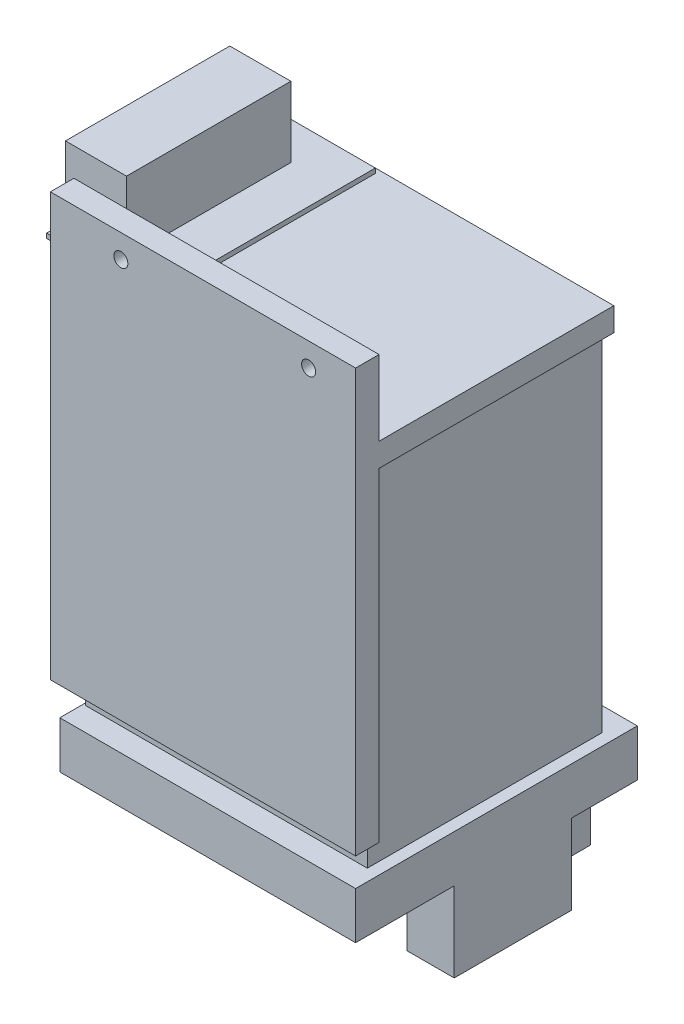
SolidWorks part; units mm, degrees
ref_plane "Front Plane" through (0, 0, 0) normal (0, 0, 1) x (1, 0, 0)
ref_plane "Top Plane" through (0, 0, 0) normal (0, 1, 0) x (1, 0, 0)
ref_plane "Right Plane" through (0, 0, 0) normal (1, 0, 0) x (0, 0, -1)
sketch "Sketch2" plane through (0, 0, 0) normal (0, 0, 1) x (1, 0, 0)
  line L1 (32.5, -45) -> (-32.5, -45)
  line L2 (32.5, -45) -> (32.5, 45)
  line L3 (32.5, 45) -> (-32.5, 45)
  line L4 (-32.5, -45) -> (-32.5, 45)
  line L5 (32.5, -45) -> (-32.5, 45) construction
  line L6 (32.5, 45) -> (-32.5, -45) construction
  circle A0 centre (-17.5, 40) radius 1.5
  circle A1 centre (22.5, 40) radius 1.5
  point P0 (0, 0)
  dimension "D3" = 40
  dimension "D4" = 3
  dimension "D5" = 5
  dimension "D6" = 10
  dimension "D1" = 65
  dimension "D2" = 90
extrude "Boss-Extrude1" add sketch "Sketch2" along normal blind 5
sketch "Sketch3" plane through (0, 0, 0) normal (0, 0, -1) x (-1, 0, 0)
  line L0 (-32.5, -45) -> (-32.5, 45) construction
  line L1 (32.5, 24) -> (-32.5, 24)
  line L2 (32.5, 24) -> (32.5, 29)
  line L3 (32.5, 29) -> (-32.5, 29)
  line L4 (-32.5, 24) -> (-32.5, 29)
  line L5 (32.5, 24) -> (-32.5, 29) construction
  line L6 (32.5, 29) -> (-32.5, 24) construction
  line L7 (-32.5, 45) -> (32.5, 45) construction
  point P0 (0, 26.5)
  dimension "D1" = 5
  dimension "D2" = 16
extrude "Boss-Extrude2" add sketch "Sketch3" along normal blind 50
sketch "Sketch4" plane through (0, 29, 0) normal (0, 1, 0) x (1, 0, 0)
  line L0 (-55, 0) -> (55, 0) construction
  line L1 (-17.2872, 2) -> (-40.2872, 2)
  line L2 (-17.2872, 2) -> (-17.2872, 49)
  line L3 (-17.2872, 49) -> (-40.2872, 49)
  line L4 (-40.2872, 2) -> (-40.2872, 49)
  line L5 (-17.2872, 2) -> (-40.2872, 49) construction
  line L6 (-17.2872, 49) -> (-40.2872, 2) construction
  point P0 (-28.7872, 25.5)
  dimension "D1" = 23
  dimension "D2" = 47
  dimension "D3" = 2
extrude "Boss-Extrude3" add sketch "Sketch4" along normal blind 1
sketch "Sketch5" plane through (0, 30, 0) normal (0, 1, 0) x (1, 0, 0)
  line L0 (-17.2872, 49) -> (-32.5, 49) construction
  line L1 (-40.2872, 41) -> (-27.2872, 41)
  line L2 (-40.2872, 41) -> (-40.2872, 6)
  line L3 (-40.2872, 6) -> (-27.2872, 6)
  line L4 (-27.2872, 41) -> (-27.2872, 6)
  line L5 (-40.2872, 41) -> (-27.2872, 6) construction
  line L6 (-40.2872, 6) -> (-27.2872, 41) construction
  line L7 (-40.2872, 49) -> (-40.2872, 2) construction
  point P0 (-33.7872, 23.5)
  dimension "D1" = 13
  dimension "D2" = 35
  dimension "D3" = 8
extrude "Boss-Extrude4" add sketch "Sketch5" along normal blind 15
sketch "Sketch6" plane through (0, 24, 0) normal (0, -1, 0) x (1, 0, 0)
  line L0 (0, -55) -> (0, 55) construction
  line L1 (30, -50) -> (-30, -50)
  line L2 (30, -50) -> (30, 0)
  line L3 (30, 0) -> (-30, 0)
  line L4 (-30, -50) -> (-30, 0)
  line L5 (30, -50) -> (-30, 0) construction
  line L6 (30, 0) -> (-30, -50) construction
  line L7 (55, 0) -> (-55, 0) construction
  line L8 (32.5, -50) -> (-32.5, -50) construction
  point P0 (0, -25)
  dimension "D1" = 60
extrude "Boss-Extrude5" add sketch "Sketch6" along normal blind 75
sketch "Sketch7" plane through (0, -51, 0) normal (0, -1, 0) x (1, 0, 0)
  line L1 (-30.5, -55) -> (32.5, -55)
  line L2 (-30.5, -55) -> (-30.5, 5)
  line L3 (-30.5, 5) -> (32.5, 5)
  line L4 (32.5, -55) -> (32.5, 5)
  line L5 (-30.5, -55) -> (32.5, 5) construction
  line L6 (-30.5, 5) -> (32.5, -55) construction
  line L7 (32.5, 5) -> (32.5, 0) construction
  line L8 (-32.5, 5) -> (32.5, 5) construction
  point P0 (1, -25)
  dimension "D1" = 63
  dimension "D2" = 60
extrude "Boss-Extrude6" add sketch "Sketch7" along normal blind 10
sketch "Sketch8" plane through (0, -61, 0) normal (0, -1, 0) x (1, 0, 0)
  line L0 (-30.5, -55) -> (32.5, -55) construction
  line L1 (22.5, -45) -> (-22.5, -45)
  line L2 (22.5, -45) -> (22.5, -55)
  line L3 (22.5, -55) -> (-22.5, -55)
  line L4 (-22.5, -45) -> (-22.5, -55)
  line L5 (22.5, -45) -> (-22.5, -55) construction
  line L6 (22.5, -55) -> (-22.5, -45) construction
  line L7 (32.5, -55) -> (32.5, 5) construction
  line L9 (22.5, -45) -> (-7.5, -45)
  line L10 (22.5, -45) -> (22.5, -27)
  line L11 (22.5, -27) -> (-7.5, -27)
  line L12 (-7.5, -45) -> (-7.5, -27)
  line L13 (22.5, -45) -> (-7.5, -27) construction
  line L14 (22.5, -27) -> (-7.5, -45) construction
  line L15 (22.5, -16) -> (32.5, -16)
  line L16 (22.5, -16) -> (22.5, -41)
  line L17 (22.5, -41) -> (32.5, -41)
  line L18 (32.5, -16) -> (32.5, -41)
  line L19 (22.5, -16) -> (32.5, -41) construction
  line L20 (22.5, -41) -> (32.5, -16) construction
  point P0 (0, -50)
  point P9 (7.5, -36)
  point P14 (27.5, -28.5)
  line M1 (32.5, -55) -> (32.5, 5)
  line M4 (-30.5, -55) -> (32.5, -55)
  dimension "D1" = 10
  dimension "D2" = 45
  dimension "D3" = 10
  dimension "D4" = 30
  dimension "D5" = 18
  dimension "D6" = 25
  dimension "D7" = 14
  dimension "D8" = 10
extrude "Boss-Extrude7" add sketch "Sketch8" along normal blind 17 contours L12 L1 L10 L11 | L1 L4 L2 M4 | L10 L17 L15 L16 M1
